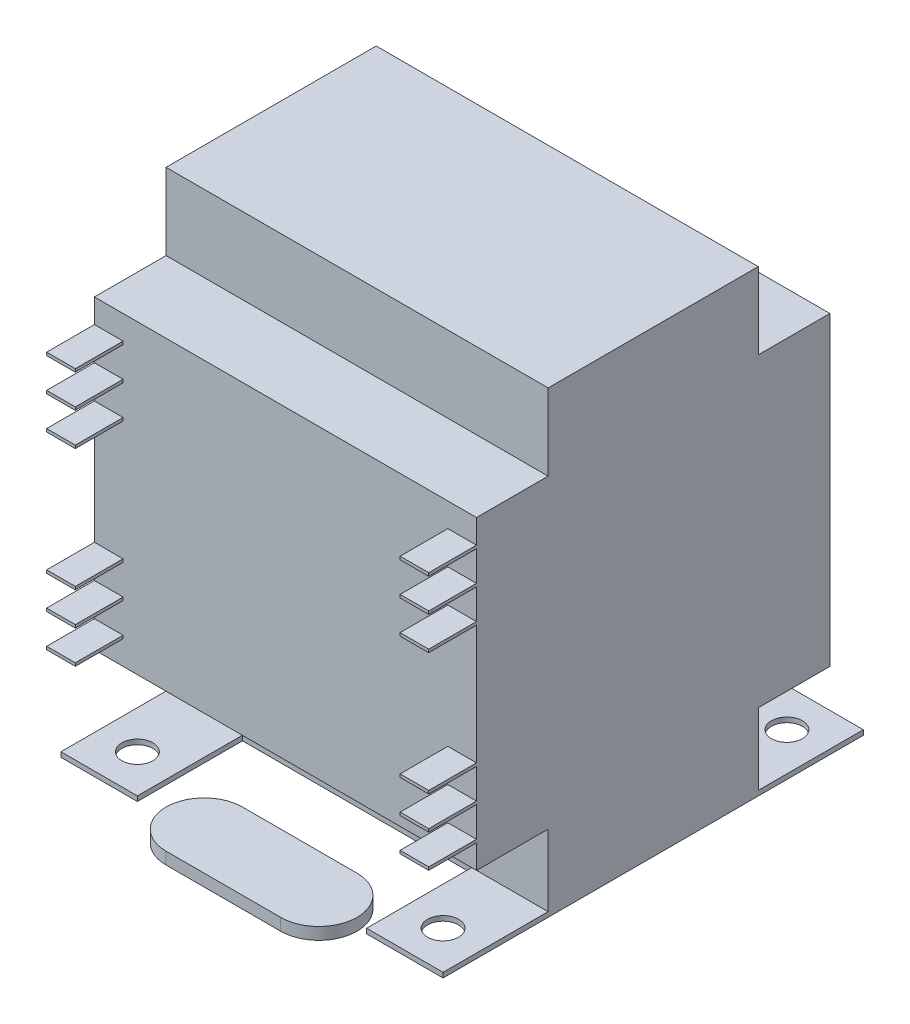
SolidWorks part; units mm, degrees
ref_plane "Front Plane" through (0, 0, 0) normal (0, 0, 1) x (1, 0, 0)
ref_plane "Top Plane" through (0, 0, 0) normal (0, 1, 0) x (1, 0, 0)
ref_plane "Right Plane" through (0, 0, 0) normal (1, 0, 0) x (0, 0, -1)
sketch "Sketch1" plane through (0, 0, 0) normal (0, 0, 1) x (1, 0, 0)
  line L1 (0, 0) -> (63.5, 0)
  line L2 (0, 0) -> (0, 76.2)
  line L3 (0, 76.2) -> (63.5, 76.2)
  line L4 (63.5, 0) -> (63.5, 76.2)
  dimension "D1" = 63.5
  dimension "D2" = 76.2
extrude "Boss-Extrude1" add sketch "Sketch1" along normal mid plane 34.925
sketch "Sketch2" plane through (0, 0, 0) normal (0, 0, 1) x (1, 0, 0)
  line L0 (0, 76.2) -> (0, 0) construction
  line L1 (0, 63.5) -> (63.5, 63.5)
  line L2 (0, 63.5) -> (0, 12.7)
  line L3 (0, 12.7) -> (63.5, 12.7)
  line L4 (63.5, 63.5) -> (63.5, 12.7)
  line L5 (63.5, 0) -> (63.5, 76.2) construction
  line L6 (63.5, 76.2) -> (0, 76.2) construction
  line L7 (0, 0) -> (63.5, 0) construction
  dimension "D1" = 12.7
  dimension "D2" = 12.7
extrude "Boss-Extrude2" add sketch "Sketch2" along normal mid plane 58.7375
sketch "Sketch3" plane through (0, 0, 0) normal (0, -1, 0) x (1, 0, 0)
  line L0 (0, 0) -> (63.5, 0) construction
  line L1 (63.5, 17.4625) -> (63.5, -17.4625) construction
  line L2 (57.15, 28.575) -> (57.15, 34.925) construction
  line L3 (57.15, -28.575) -> (6.35, -28.575) construction
  line L4 (57.15, -28.575) -> (57.15, 28.575) construction
  line L5 (57.15, 28.575) -> (6.35, 28.575) construction
  line L6 (6.35, -28.575) -> (6.35, 28.575) construction
  line L7 (57.15, -28.575) -> (6.35, 28.575) construction
  line L8 (57.15, 28.575) -> (6.35, -28.575) construction
  line L9 (63.5, 17.4625) -> (50.8, 17.4625)
  line L10 (63.5, 17.4625) -> (63.5, 34.925)
  line L11 (63.5, 34.925) -> (50.8, 34.925)
  line L12 (50.8, 17.4625) -> (50.8, 34.925)
  line L13 (57.15, 33.3375) -> (57.15, 23.8125) construction
  line L14 (63.5, -34.925) -> (50.8, -34.925)
  line L15 (63.5, -17.4625) -> (50.8, -17.4625)
  line L16 (63.5, -17.4625) -> (63.5, -34.925)
  line L17 (50.8, -17.4625) -> (50.8, -34.925)
  line L18 (31.75, 0) -> (31.75, 28.575) construction
  line L19 (0, -17.4625) -> (0, -34.925)
  line L20 (0, -17.4625) -> (12.7, -17.4625)
  line L21 (12.7, -17.4625) -> (12.7, -34.925)
  line L22 (0, -34.925) -> (12.7, -34.925)
  line L23 (0, 34.925) -> (12.7, 34.925)
  line L24 (0, 17.4625) -> (0, 34.925)
  line L25 (0, 17.4625) -> (12.7, 17.4625)
  line L26 (12.7, 17.4625) -> (12.7, 34.925)
  circle A0 centre (6.35, 28.575) radius 2.5797
  circle A1 centre (57.15, 28.575) radius 2.5797
  circle A2 centre (57.15, -28.575) radius 2.5797
  circle A3 centre (6.35, -28.575) radius 2.5797
  point P5 (31.75, 0)
  point P22 (57.15, 28.575)
  dimension "D3" = 5.1594
  dimension "D1" = 57.15
  dimension "D2" = 50.8
  dimension "D4" = 9.525
  dimension "D5" = 17.4625
extrude "Boss-Extrude3" add sketch "Sketch3" against normal blind 0.8128
sketch "Sketch4" plane through (0, 0, 29.3687) normal (0, 0, 1) x (1, 0, 0)
  line L0 (0, 63.5) -> (0, 12.7) construction
  line L1 (0, 59.5207) -> (4.7625, 59.5207)
  line L2 (0, 59.5207) -> (0, 59.0127)
  line L3 (0, 59.0127) -> (4.7625, 59.0127)
  line L4 (4.7625, 59.5207) -> (4.7625, 59.0127)
  line L5 (31.75, 63.5) -> (31.75, 12.7) construction
  line L6 (63.5, 63.5) -> (0, 63.5) construction
  line L7 (0, 12.7) -> (63.5, 12.7) construction
  line L8 (31.75, 38.1) -> (0, 38.1) construction
  line L9 (4.7625, 59.2667) -> (0, 59.2667) construction
  line L10 (2.3813, 59.2667) -> (2.3813, 38.1) construction
  line L11 (0, 54.0216) -> (4.7625, 54.0216)
  line L12 (4.7625, 54.0216) -> (4.7625, 53.5136)
  line L13 (0, 53.5136) -> (4.7625, 53.5136)
  line L14 (0, 54.0216) -> (0, 53.5136)
  line L15 (0, 48.5225) -> (4.7625, 48.5225)
  line L16 (4.7625, 48.5225) -> (4.7625, 48.0145)
  line L17 (0, 48.0145) -> (4.7625, 48.0145)
  line L18 (0, 48.5225) -> (0, 48.0145)
  line L19 (58.7375, 59.2667) -> (63.5, 59.2667) construction
  line L20 (63.5, 48.5225) -> (63.5, 48.0145)
  line L21 (63.5, 48.0145) -> (58.7375, 48.0145)
  line L22 (58.7375, 48.5225) -> (58.7375, 48.0145)
  line L23 (63.5, 48.5225) -> (58.7375, 48.5225)
  line L24 (63.5, 54.0216) -> (63.5, 53.5136)
  line L25 (63.5, 53.5136) -> (58.7375, 53.5136)
  line L26 (58.7375, 54.0216) -> (58.7375, 53.5136)
  line L27 (63.5, 54.0216) -> (58.7375, 54.0216)
  line L28 (63.5, 59.5207) -> (63.5, 59.0127)
  line L29 (63.5, 59.0127) -> (58.7375, 59.0127)
  line L30 (58.7375, 59.5207) -> (58.7375, 59.0127)
  line L31 (63.5, 59.5207) -> (58.7375, 59.5207)
  line L32 (58.7375, 16.9333) -> (63.5, 16.9333) construction
  line L33 (4.7625, 16.9333) -> (0, 16.9333) construction
  line L34 (63.5, 16.6793) -> (58.7375, 16.6793)
  line L35 (58.7375, 16.6793) -> (58.7375, 17.1873)
  line L36 (63.5, 17.1873) -> (58.7375, 17.1873)
  line L37 (63.5, 16.6793) -> (63.5, 17.1873)
  line L38 (63.5, 22.1784) -> (58.7375, 22.1784)
  line L39 (58.7375, 22.1784) -> (58.7375, 22.6864)
  line L40 (63.5, 22.6864) -> (58.7375, 22.6864)
  line L41 (63.5, 22.1784) -> (63.5, 22.6864)
  line L42 (63.5, 27.6775) -> (58.7375, 27.6775)
  line L43 (58.7375, 27.6775) -> (58.7375, 28.1855)
  line L44 (63.5, 28.1855) -> (58.7375, 28.1855)
  line L45 (63.5, 27.6775) -> (63.5, 28.1855)
  line L46 (0, 27.6775) -> (0, 28.1855)
  line L47 (0, 28.1855) -> (4.7625, 28.1855)
  line L48 (4.7625, 27.6775) -> (4.7625, 28.1855)
  line L49 (0, 27.6775) -> (4.7625, 27.6775)
  line L50 (0, 22.1784) -> (0, 22.6864)
  line L51 (0, 22.6864) -> (4.7625, 22.6864)
  line L52 (4.7625, 22.1784) -> (4.7625, 22.6864)
  line L53 (0, 22.1784) -> (4.7625, 22.1784)
  line L54 (4.7625, 16.6793) -> (4.7625, 17.1873)
  line L55 (0, 17.1873) -> (4.7625, 17.1873)
  line L56 (0, 16.6793) -> (0, 17.1873)
  line L57 (0, 16.6793) -> (4.7625, 16.6793)
  dimension "D1" = 4.7625
  dimension "D2" = 0.508
  dimension "D3" = 21.1667
  dimension "D4" = 25.4
  dimension "D5" = 3
extrude "Boss-Extrude4" add sketch "Sketch4" along normal blind 7.9375
sketch "Sketch5" plane through (0, 0, 0) normal (0, -1, 0) x (-1, 0, 0)
  line L0 (-31.75, -33.3375) -> (-31.75, 0) construction
  line L1 (-31.75, 0) -> (0, 0) construction
  line L2 (-63.5, 0) -> (-31.75, 0) construction
  line L3 (-63.5, -34.925) -> (-63.5, 34.925) construction
  line L4 (-41.275, -39.6875) -> (-22.225, -39.6875)
  line L5 (-22.225, -26.9875) -> (-41.275, -26.9875)
  circle A0 centre (-31.75, -33.3375) radius 6.35 construction
  arc A1 (-22.225, -39.6875) -> (-22.225, -26.9875) centre (-22.225, -33.3375) ccw
  arc A2 (-41.275, -39.6875) -> (-41.275, -26.9875) centre (-41.275, -33.3375) cw
  point P14 (-31.75, -26.9875)
  point P16 (-31.75, -39.6875)
  dimension "D1" = 12.7
  dimension "D2" = 33.3375
  dimension "D3" = 19.05
extrude "Boss-Extrude5" add sketch "Sketch5" along normal blind 2 separate body
